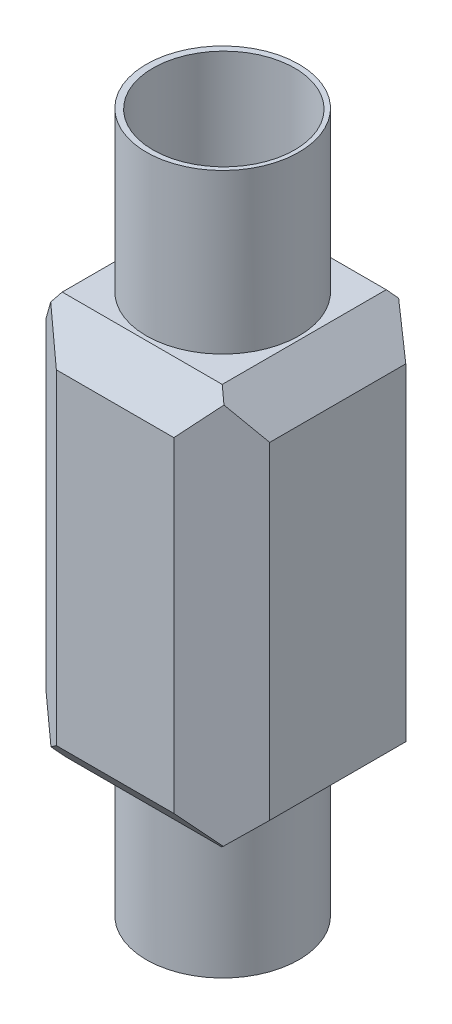
SolidWorks part; units mm, degrees
ref_plane "Front Plane" through (0, 0, 0) normal (0, 0, 1) x (1, 0, 0)
ref_plane "Top Plane" through (0, 0, 0) normal (0, 1, 0) x (1, 0, 0)
ref_plane "Right Plane" through (0, 0, 0) normal (1, 0, 0) x (0, 0, -1)
sketch "Sketch1" plane through (0, 0, 0) normal (0, 1, 0) x (1, 0, 0)
  line L1 (0, 0) -> (-100, 0)
  line L2 (0, 0) -> (0, 100)
  line L3 (0, 100) -> (-100, 100)
  line L4 (-100, 0) -> (-100, 100)
  dimension "D1" = 100
  dimension "D2" = 100
extrude "Boss-Extrude1" add sketch "Sketch1" along normal blind 180
sketch "Sketch2" plane through (0, 180, 0) normal (0, 1, 0) x (1, 0, 0)
  circle A0 centre (-51.3773, 49.0765) radius 34.2578
  point P2 (-49.1037, 52.2166)
  point P3 (-48.8771, 51.8469)
  point P4 (-51.3773, 49.0765)
extrude "Boss-Extrude2" add sketch "Sketch2" along normal mid plane 700
sketch "Sketch3" plane through (0, 0, 0) normal (1, 0, 0) x (0, 0, -1)
  line L1 (-18.5833, 361.0481) -> (133.4231, 361.0481)
  line L2 (-18.5833, 361.0481) -> (-18.5833, 643.5005)
  line L3 (-18.5833, 643.5005) -> (133.4231, 643.5005)
  line L4 (133.4231, 361.0481) -> (133.4231, 643.5005)
extrude "Cut-Extrude2" cut sketch "Sketch3" against normal blind 400
sketch "Sketch4" plane through (0, 0, 0) normal (1, 0, 0) x (0, 0, -1)
  line L0 (12.982, 0) -> (-8.9942, 25.8281)
  line L1 (-8.9942, 25.8281) -> (-18.5645, -15.2595)
  line L2 (-18.5645, -15.2595) -> (12.982, 0)
  line L3 (85.0725, -1.4481) -> (109.2376, 19.1131)
  line L4 (109.2376, 19.1131) -> (115.92, -3.2674)
  line L5 (115.92, -3.2674) -> (85.0725, -1.4481)
  line L6 (12.982, 180) -> (-8.9942, 148.5376)
  line L7 (-8.9942, 148.5376) -> (-15.4182, 193.2193)
  line L8 (-15.4182, 193.2193) -> (12.982, 180)
  line L9 (85.0725, 181.8543) -> (103.8412, 159.7959)
  line L10 (103.8412, 159.7959) -> (106.1325, 198.6474)
  line L11 (106.1325, 198.6474) -> (85.0725, 181.8543)
extrude "Cut-Extrude3" cut sketch "Sketch4" against normal blind 400
sketch "Sketch5" plane through (0, 0, 0) normal (0, 0, 1) x (1, 0, 0)
  line L0 (-85.6233, 0) -> (-106.3704, 21.4264)
  line L1 (-106.3704, 21.4264) -> (-122.2889, 3.2093)
  line L2 (-122.2889, 3.2093) -> (-93.5263, -19.8847)
  line L3 (-93.5263, -19.8847) -> (-85.6233, 0)
  line L4 (-15.695, 0) -> (0, 15.2574)
  line L5 (0, 15.2574) -> (12.1227, 15.2574)
  line L6 (12.1227, 15.2574) -> (10.5631, -19.8847)
  line L7 (10.5631, -19.8847) -> (-15.695, 0)
  line L8 (-87.1665, 180.2481) -> (-106.3704, 151.2911)
  line L9 (-106.3704, 151.2911) -> (-117.7055, 200.5011)
  line L10 (-117.7055, 200.5011) -> (-87.1665, 180.2481)
  line L11 (-15.695, 180.2481) -> (7.8338, 153.2796)
  line L12 (7.8338, 153.2796) -> (0, 193.9412)
  line L13 (0, 193.9412) -> (-15.695, 180.2481)
extrude "Cut-Extrude4" cut sketch "Sketch5" against normal blind 400
sketch "Sketch6" plane through (0, 180, 0) normal (0, 1, 0) x (1, 0, 0)
  line L1 (-112.387, 28.4004) -> (-64.2613, -10.2128)
  line L2 (-112.387, 28.4004) -> (-124.6497, -15.5119)
  line L3 (-124.6497, -15.5119) -> (-84.4064, -15.5119)
  line L4 (-64.2613, -10.2128) -> (-84.4064, -15.5119)
  line L5 (-97.0655, 135.8618) -> (-119.3755, 77.7927)
  line L6 (-97.0655, 135.8618) -> (-66.4287, 110.5752)
  line L7 (-66.4287, 110.5752) -> (-118.0433, 64.3476)
  line L8 (-119.3755, 77.7927) -> (-118.0433, 64.3476)
  line L9 (-24.6964, -21.8158) -> (11.0921, -8.9736)
  line L10 (-24.6964, -21.8158) -> (-38.5316, -11.1392)
  line L11 (-38.5316, -11.1392) -> (17.4283, 32.3938)
  line L12 (11.0921, -8.9736) -> (17.4283, 32.3938)
  line L13 (-17.4455, 140.8044) -> (35.4175, 107.2625)
  line L14 (-17.4455, 140.8044) -> (-31.7244, 103.6253)
  line L15 (-31.7244, 103.6253) -> (9.3055, 72.9964)
  line L16 (35.4175, 107.2625) -> (9.3055, 72.9964)
  point P4 (-17.4455, 140.8044)
  point P5 (-30.2763, 114.984)
  point P6 (35.4175, 107.2625)
  point P19 (-30.6265, 106.484)
  point P20 (-11.2095, 88.3109)
extrude "Cut-Extrude5" cut sketch "Sketch6" against normal blind 400
sketch "Sketch7" plane through (0, 0, 0) normal (0, 0, 1) x (1, 0, 0)
  line L1 (-146.2029, -210.0437) -> (13.9564, -210.0437)
  line L2 (-146.2029, -210.0437) -> (-146.2029, -62.6814)
  line L3 (-146.2029, -62.6814) -> (13.9564, -62.6814)
  line L4 (13.9564, -210.0437) -> (13.9564, -62.6814)
extrude "Cut-Extrude6" cut sketch "Sketch7" against normal blind 400
sketch "Sketch8" plane through (0, 0, 0) normal (0, 0, 1) x (1, 0, 0)
  line L1 (-127.1965, 251.4288) -> (20.1142, 251.4288)
  line L2 (-127.1965, 251.4288) -> (-127.1965, 413.4677)
  line L3 (-127.1965, 413.4677) -> (20.1142, 413.4677)
  line L4 (20.1142, 251.4288) -> (20.1142, 413.4677)
extrude "Cut-Extrude7" cut sketch "Sketch8" against normal blind 400
sketch "Sketch9" plane through (0, 251.4288, 0) normal (0, 1, 0) x (1, 0, 0)
  circle A0 centre (-50.809, 49.032) radius 31.8473
  point P2 (-50.6049, 49.6989)
  point P3 (-51.6378, 48.9774)
  point P4 (-50.809, 49.032)
extrude "Cut-Extrude8" cut sketch "Sketch9" against normal blind 400
